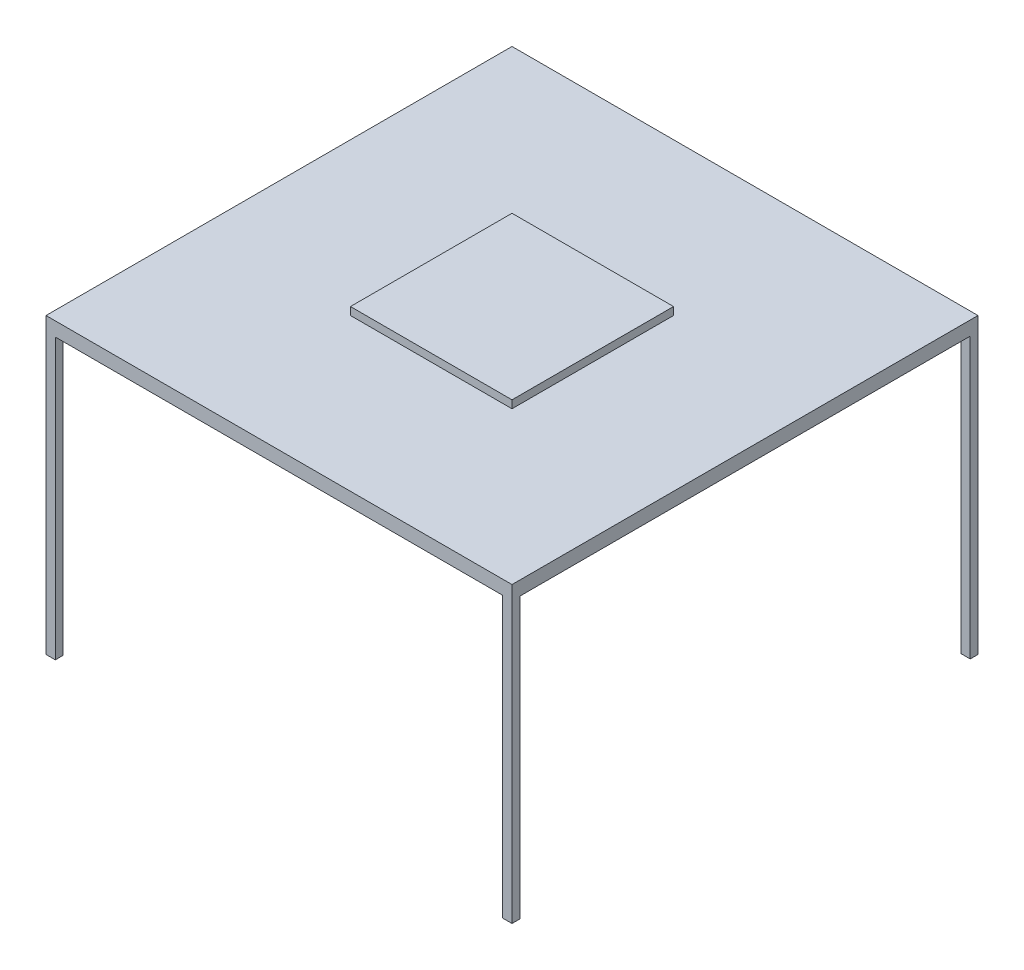
SolidWorks part; units mm, degrees
ref_plane "Front Plane" through (0, 0, 0) normal (0, 0, 1) x (1, 0, 0)
ref_plane "Top Plane" through (0, 0, 0) normal (0, 1, 0) x (1, 0, 0)
ref_plane "Right Plane" through (0, 0, 0) normal (1, 0, 0) x (0, 0, -1)
sketch "Sketch1" plane through (0, 0, 0) normal (0, 1, 0) x (1, 0, 0)
  line L1 (-260, -260) -> (260, -260)
  line L2 (-260, -260) -> (-260, 260)
  line L3 (-260, 260) -> (260, 260)
  line L4 (260, -260) -> (260, 260)
  line L5 (-260, -260) -> (260, 260) construction
  line L6 (-260, 260) -> (260, -260) construction
  text T0 "CHESS board"
  point P0 (0, 0)
  dimension "D1" = 520
  dimension "D2" = 520
extrude "Boss-Extrude1" add sketch "Sketch1" along normal blind 25 contours L1 L4 L3 L2
sketch "Sketch2" plane through (0, 0, 0) normal (0, -1, 0) x (1, 0, 0)
  line L1 (750, 750) -> (-750, 750)
  line L2 (750, 750) -> (750, -750)
  line L3 (750, -750) -> (-750, -750)
  line L4 (-750, 750) -> (-750, -750)
  line L5 (750, 750) -> (-750, -750) construction
  line L6 (750, -750) -> (-750, 750) construction
  point P0 (0, 0)
  dimension "D1" = 1500
  dimension "D2" = 1500
extrude "Boss-Extrude2" add sketch "Sketch2" along normal blind 45
sketch "Sketch3" plane through (0, -45, 0) normal (0, -1, 0) x (1, 0, 0)
  line L0 (750, 750) -> (720, 750)
  line L1 (750, 750) -> (-750, 750) construction
  line L2 (720, 750) -> (720, 725)
  line L3 (720, 725) -> (750, 725)
  line L4 (750, -750) -> (750, 750) construction
  line L5 (750, 725) -> (750, 750)
  dimension "D1" = 25
  dimension "D2" = 30
extrude "Boss-Extrude3" add sketch "Sketch3" along normal blind 900
sketch "Sketch4" plane through (0, -45, 0) normal (0, -1, 0) x (1, 0, 0)
  line L0 (-750, 725) -> (-750, 750)
  line L1 (-750, 750) -> (-750, -750) construction
  line L2 (-750, 750) -> (-720, 750)
  line L3 (720, 750) -> (-750, 750) construction
  line L4 (-720, 750) -> (-720, 725)
  line L5 (-720, 725) -> (-750, 725)
  dimension "D1" = 25
  dimension "D2" = 30
extrude "Boss-Extrude4" add sketch "Sketch4" along normal blind 900
sketch "Sketch5" plane through (0, -45, 0) normal (0, -1, 0) x (1, 0, 0)
  line L0 (750, -750) -> (720, -750)
  line L1 (-750, -750) -> (750, -750) construction
  line L2 (720, -750) -> (720, -725)
  line L3 (720, -725) -> (750, -725)
  line L4 (750, -750) -> (750, 725) construction
  line L5 (750, -725) -> (750, -750)
  dimension "D1" = 25
  dimension "D2" = 30
extrude "Boss-Extrude5" add sketch "Sketch5" along normal blind 900
sketch "Sketch6" plane through (0, -45, 0) normal (0, -1, 0) x (1, 0, 0)
  line L0 (-725, -750) -> (-750, -750)
  line L1 (-750, -750) -> (720, -750) construction
  line L2 (-750, -750) -> (-750, -720)
  line L3 (-750, 725) -> (-750, -750) construction
  line L4 (-750, -720) -> (-725, -720)
  line L5 (-725, -720) -> (-725, -750)
  dimension "D1" = 25
  dimension "D2" = 30
extrude "Boss-Extrude6" add sketch "Sketch6" along normal blind 900
